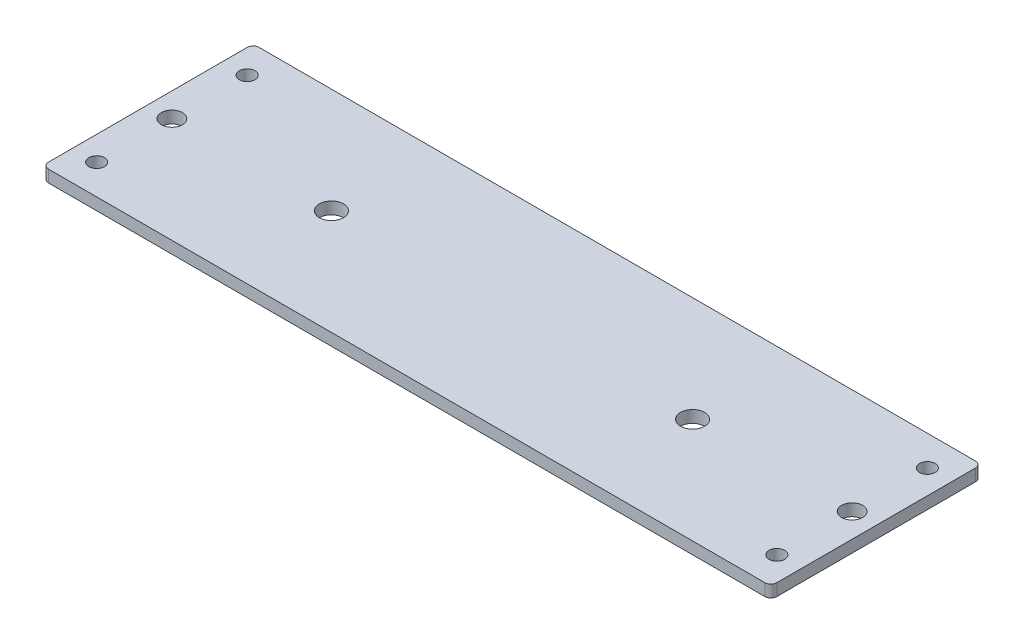
SolidWorks part; units mm, degrees
ref_plane "前视基准面" through (0, 0, 0) normal (0, 0, 1) x (1, 0, 0)
ref_plane "上视基准面" through (0, 0, 0) normal (0, 1, 0) x (1, 0, 0)
ref_plane "右视基准面" through (0, 0, 0) normal (1, 0, 0) x (0, 0, -1)
sketch "草图1" plane through (0, 0, 0) normal (0, 1, 0) x (1, 0, 0)
  line L1 (-121, 35) -> (121, 35)
  line L2 (-121, 35) -> (-121, -35)
  line L3 (-121, -35) -> (121, -35)
  line L4 (121, 35) -> (121, -35)
  line L5 (-121, 35) -> (121, -35) construction
  line L6 (-121, -35) -> (121, 35) construction
  point P1 (0, 0)
  dimension "D1" = 242
  dimension "D2" = 70
extrude "凸台-拉伸1" add sketch "草图1" along normal blind 4
sketch "草图2" plane through (0, 4, 0) normal (0, 1, 0) x (1, 0, 0)
  line L0 (-121, 0) -> (121, 0) construction
  line L1 (-121, 35) -> (-121, -35) construction
  line L2 (121, -35) -> (121, 35) construction
  line L3 (0, 35) -> (0, -35) construction
  line L4 (121, 35) -> (-121, 35) construction
  line L5 (-121, -35) -> (121, -35) construction
  line L7 (-113, -25) -> (-113, 25) construction
  line L8 (121, 35) -> (-121, 35) construction
  circle A10 centre (-113, 25) radius 2.6
  circle A11 centre (-113, -25) radius 2.6
  circle A12 centre (113, -25) radius 2.6
  circle A13 centre (113, 25) radius 2.6
  circle A19 centre (-60, 0) radius 4
  circle A20 centre (60, 0) radius 4
  circle A21 centre (-113, 0) radius 3.5
  circle A22 centre (113, 0) radius 3.5
  point P18 (-60, 0)
  dimension "D2" = 10
  dimension "D3" = 8
  dimension "D7" = 5.2
  dimension "D10" = 8
  dimension "D11" = 60
extrude "切除-拉伸1" cut sketch "草图2" against normal blind 4
fillet "圆角1" radius 2 4 edges at (121, 2, -35) (121, 2, 35) (-121, 2, 35) (-121, 2, -35)
